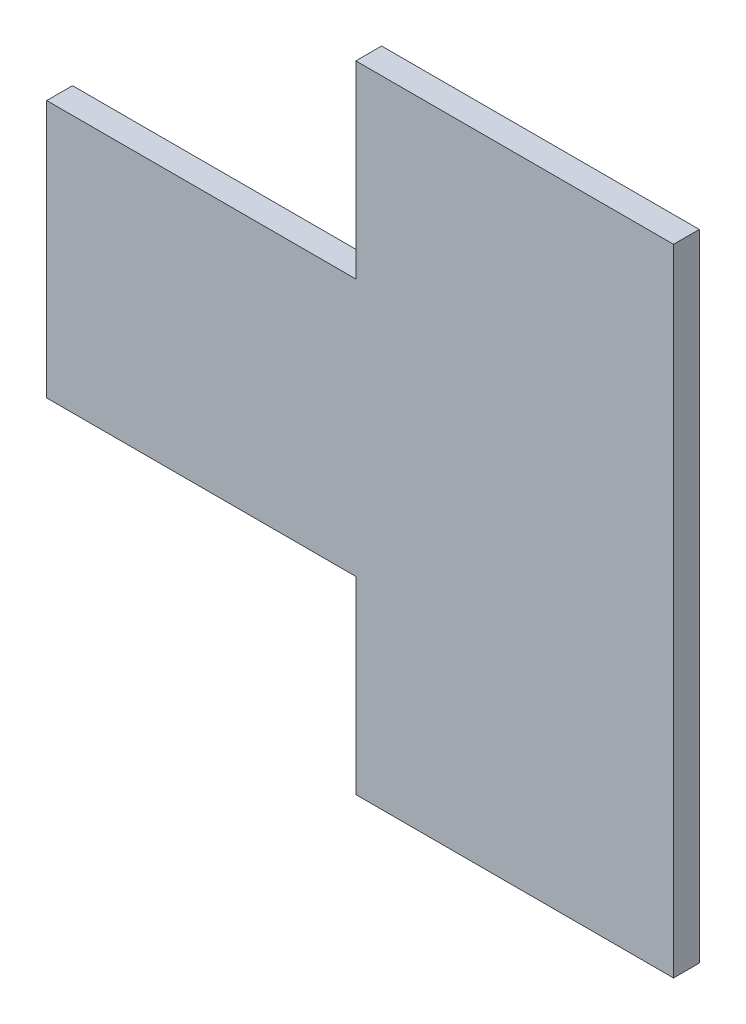
SolidWorks part; units mm, degrees
ref_plane "前视基准面" through (0, 0, 0) normal (0, 0, 1) x (1, 0, 0)
ref_plane "上视基准面" through (0, 0, 0) normal (0, 1, 0) x (1, 0, 0)
ref_plane "右视基准面" through (0, 0, 0) normal (1, 0, 0) x (0, 0, -1)
other "Configuration Table"
sketch "草图1" plane through (0, 0, 0) normal (0, 0, 1) x (1, 0, 0)
  line L0 (0, 0) -> (36, 0)
  line L1 (36, 0) -> (36, 22)
  line L2 (36, 22) -> (73, 22)
  line L3 (73, 22) -> (73, -52)
  line L4 (73, -52) -> (36, -52)
  line L5 (36, -52) -> (36, -30)
  line L6 (36, -30) -> (0, -30)
  line L7 (0, -30) -> (0, 0)
  dimension "D1" = 30
  dimension "D2" = 36
  dimension "D3" = 22
  dimension "D4" = 37
extrude "凸台-拉伸1" add sketch "草图1" along normal blind 3
